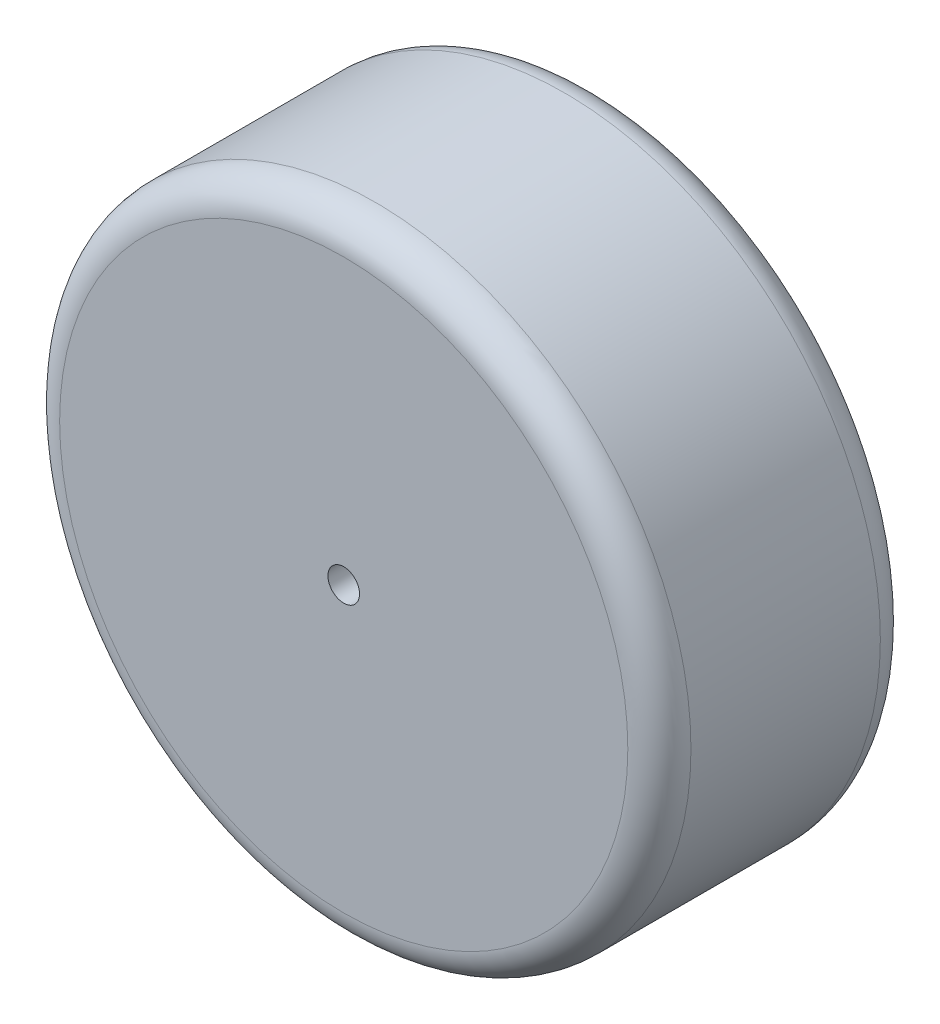
SolidWorks part; units mm, degrees
material "Rubber"
ref_plane "Front Plane" through (0, 0, 0) normal (0, 0, 1) x (1, 0, 0)
ref_plane "Top Plane" through (0, 0, 0) normal (0, 1, 0) x (1, 0, 0)
ref_plane "Right Plane" through (0, 0, 0) normal (1, 0, 0) x (0, 0, -1)
sketch "Sketch1" plane through (0, 0, 0) normal (0, 0, 1) x (1, 0, 0)
  circle A0 centre (0, 0) radius 100
  circle A1 centre (0, 0) radius 5
  dimension "D1" = 200
  dimension "D2" = 10
extrude "Boss-Extrude1" add sketch "Sketch1" along normal blind 80
fillet "Fillet1" radius 10 2 edges at (100, 0, 0) (100, 0, 80)
